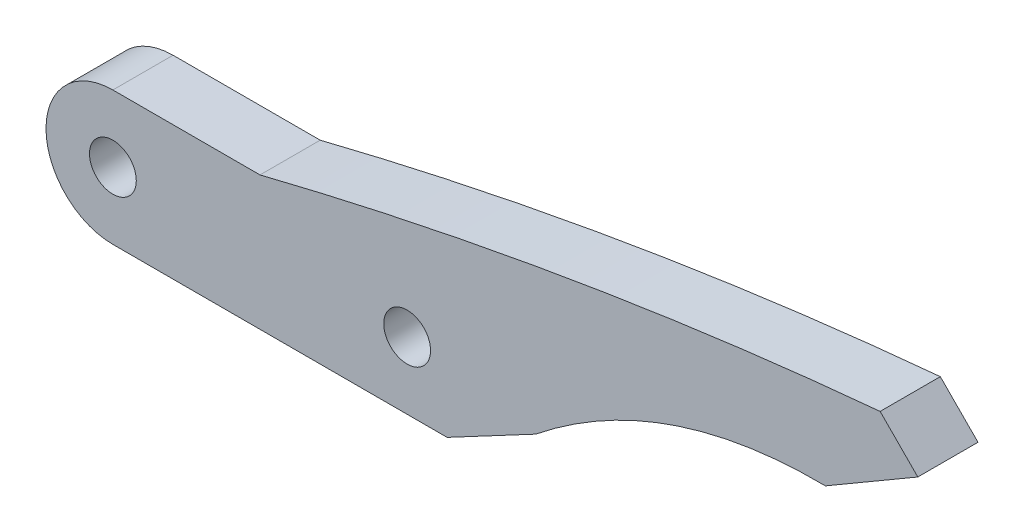
SolidWorks part; units mm, degrees
ref_plane "Front Plane" through (0, 0, 0) normal (0, 0, 1) x (1, 0, 0)
ref_plane "Top Plane" through (0, 0, 0) normal (0, 1, 0) x (1, 0, 0)
ref_plane "Right Plane" through (0, 0, 0) normal (1, 0, 0) x (0, 0, -1)
sketch "Sketch2" plane through (0, 0, 0) normal (0, 0, 1) x (1, 0, 0)
  line L0 (-11, 0) -> (11, 0) construction
  line L1 (0, 0) -> (0, -3.0482) construction
  line L3 (-17.4754, -5) -> (17.4754, -5)
  line L4 (-17.4754, -5) -> (-17.4754, 5)
  line L5 (-17.4754, 5) -> (17.4754, 5)
  line L6 (17.4754, -5) -> (17.4754, 5)
  line L7 (-17.4754, -5) -> (17.4754, 5) construction
  line L8 (-17.4754, 5) -> (17.4754, -5) construction
  circle A0 centre (-11, 0) radius 5
  circle A1 centre (-11, 0) radius 1.75
  circle A2 centre (11, 0) radius 1.75
  circle A3 centre (11, 0) radius 5
  point P4 (0, 0)
  dimension "D2" = 3.5
  dimension "D3" = 10
  dimension "D1" = 22
extrude "Boss-Extrude1" add sketch "Sketch2" against normal blind 4.5 contours A0 A1 | A3 A2 | L3 A3 L5 A0
sketch "Sketch3" plane through (0, 0, 0) normal (0, 0, 1) x (1, 0, 0)
  line L0 (46.364, 12.87) -> (49.1808, 10.03)
  line L1 (49.1808, 10.03) -> (42.27, 6)
  line L2 (-11, -5) -> (11, -5) construction
  line L3 (11, 0) -> (11, -5) construction
  line L4 (20.61, -1.48) -> (13.99, -5)
  line L5 (13.99, -5) -> (11, -5)
  line L6 (-11, 5) -> (11, 5) construction
  line L7 (0, 5) -> (11, 5)
  arc A0 (11, -5) -> (11, 5) centre (11, 0) ccw construction
  arc A1 (11, -5) -> (11, 5) centre (11, 0) ccw
  spline S0 degree 2 poles (42.27, 6) (30.1462, 6.1573) (20.61, -1.48) knots 0 0 0 1 1 1
  spline S1 degree 2 poles (0, 5) (22.8855, 10.7079) (46.364, 12.87) knots 0 0 0 1 1 1
  dimension "D1" = 4
  dimension "D2" = 8
  dimension "D3" = 17.87
  dimension "D4" = 15.03
  dimension "D5" = 11
  dimension "D6" = 9.45
  dimension "D7" = 3.52
  dimension "D8" = 9.61
  dimension "D9" = 20.52
  dimension "D10" = 31.27
  dimension "D11" = 2.99
  dimension "D12" = 6.62
  dimension "D13" = 28.001
  dimension "D14" = 13.52
  dimension "D15" = 15.07
extrude "Boss-Extrude2" add sketch "Sketch3" against normal up to surface (4.5 mm away) up to face at (-9.25, 0, -4.5)
